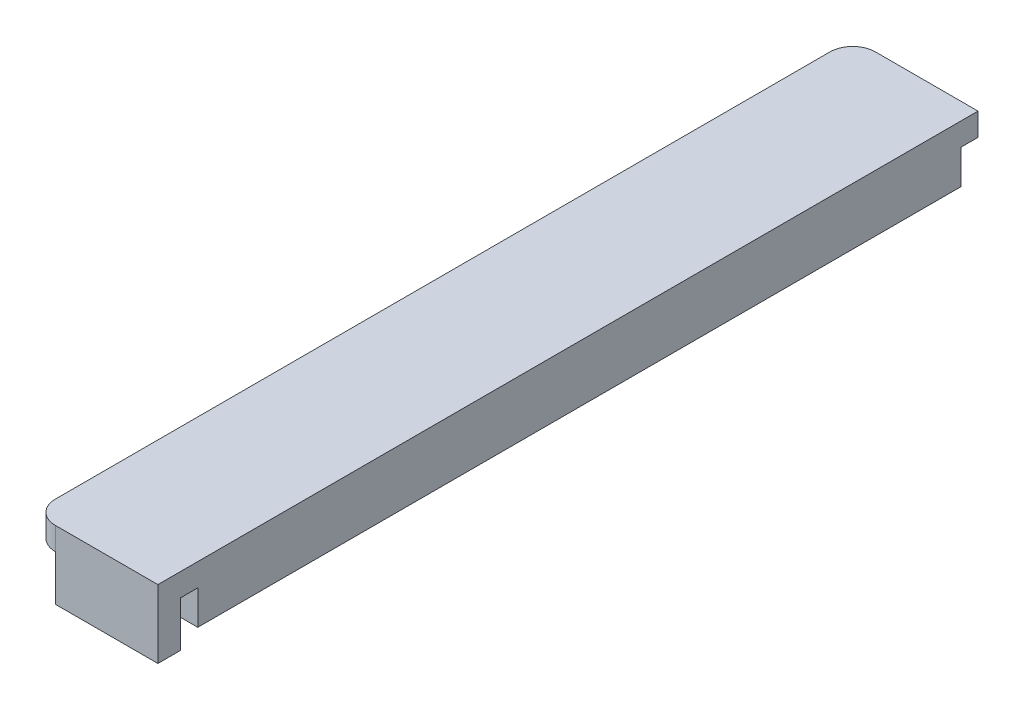
SolidWorks part; units mm, degrees
ref_plane "前视基准面" through (0, 0, 0) normal (0, 0, 1) x (1, 0, 0)
ref_plane "上视基准面" through (0, 0, 0) normal (0, 1, 0) x (1, 0, 0)
ref_plane "右视基准面" through (0, 0, 0) normal (1, 0, 0) x (0, 0, -1)
other "Configuration Table"
sketch "草图1" plane through (0, 0, 0) normal (0, 1, 0) x (1, 0, 0)
  line L1 (-3.5, 37) -> (5.5, 37)
  line L2 (-5.5, 35) -> (-5.5, -35)
  line L3 (-3.5, -37) -> (5.5, -37)
  line L4 (5.5, 37) -> (5.5, -37)
  line L5 (-5.5, 37) -> (5.5, -37) construction
  line L6 (-5.5, -37) -> (5.5, 37) construction
  arc A0 (-3.5, 37) -> (-5.5, 35) centre (-3.5, 35) ccw
  arc A1 (-5.5, -35) -> (-3.5, -37) centre (-3.5, -35) ccw
  point P0 (0, 0)
  dimension "D3" = 2
  dimension "D4" = 2
  dimension "D1" = 11
  dimension "D2" = 74
extrude "凸台-拉伸1" add sketch "草图1" along normal blind 2
sketch "草图2" plane through (0, 0, 0) normal (0, -1, 0) x (1, 0, 0)
  line L0 (5.5, 37) -> (5.5, -37) construction
  line L1 (-3.5, 37) -> (5.5, 37)
  line L2 (-3.5, 37) -> (-3.5, 35)
  line L3 (-3.5, 35) -> (5.5, 35)
  line L4 (5.5, 37) -> (5.5, 35)
  line L6 (-3.5, -37) -> (5.5, -37)
  line L7 (-3.5, -37) -> (-3.5, -35)
  line L8 (-3.5, -35) -> (5.5, -35)
  line L9 (5.5, -37) -> (5.5, -35)
  point P7 (1, 35)
  dimension "D1" = 2
  dimension "D2" = 2
extrude "凸台-拉伸2" add sketch "草图2" along normal blind 4
sketch "草图3" plane through (0, 0, 0) normal (0, -1, 0) x (1, 0, 0)
  line L6 (-3.5, 35) -> (5.5, 35) construction
  line L7 (5.5, 35) -> (5.5, -35) construction
  line L8 (5.5, 33.5) -> (-4, 33.5)
  line L9 (5.5, 33.5) -> (5.5, -33.5)
  line L10 (5.5, -33.5) -> (-4, -33.5)
  line L11 (-4, 33.5) -> (-4, -33.5)
  line L12 (-5.5, -35) -> (-5.5, 35) construction
  line L13 (5.5, -35) -> (-3.5, -35) construction
  dimension "D1" = 1.5
  dimension "D2" = 1.5
  dimension "D3" = 1.5
extrude "凸台-拉伸3" add sketch "草图3" along normal blind 3
sketch "草图4" plane through (0, -4, 0) normal (0, -1, 0) x (1, 0, 0)
  line L1 (5.5, -37) -> (-10.5045, -37)
  line L2 (5.5, -37) -> (5.5, -35)
  line L3 (5.5, -35) -> (-10.5045, -35)
  line L4 (-10.5045, -37) -> (-10.5045, -35)
extrude "切除-拉伸1" cut sketch "草图4" against normal blind 10
fillet "圆角1" radius 2 1 edges at (-5.5, 1, -35)
